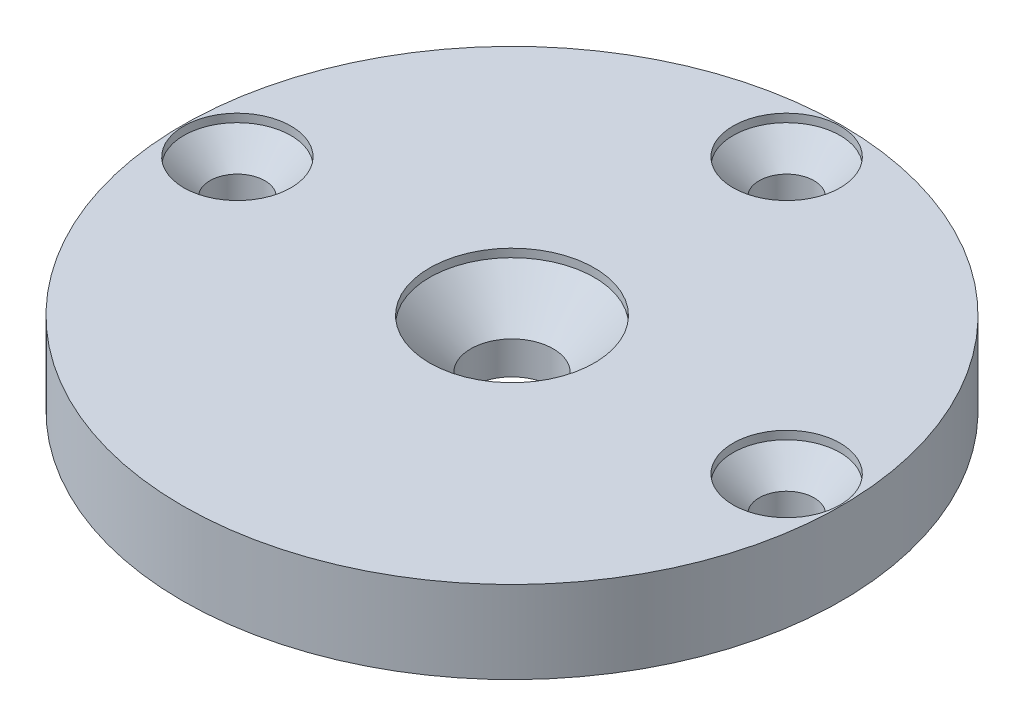
SolidWorks part; units mm, degrees
ref_plane "Front Plane" through (0, 0, 0) normal (0, 0, 1) x (1, 0, 0)
ref_plane "Top Plane" through (0, 0, 0) normal (0, 1, 0) x (1, 0, 0)
ref_plane "Right Plane" through (0, 0, 0) normal (1, 0, 0) x (0, 0, -1)
sketch "Sketch1" plane through (0, 0, 0) normal (0, 1, 0) x (1, 0, 0)
  circle A0 centre (0, 0) radius 12
  circle A1 centre (0, 0) radius 1.5
  circle A2 centre (0, 0) radius 10
  circle A3 centre (-10, 0) radius 1
  circle A4 centre (0, 10) radius 1
  circle A5 centre (10, 0) radius 1
  dimension "D1" = 24
  dimension "D2" = 3
  dimension "D3" = 20
  dimension "D4" = 2
extrude "Boss-Extrude1" add sketch "Sketch1" along normal blind 3 contours A0 A5 A2 A3 A4 | A5 A2 A4 A3 A1
hole_wizard "CSK for M2 Flat Head Machine Screw1" positions "Sketch2" profile "Sketch3" countersink size "M2" standard "ANSI Metric"
sketch "Sketch2" plane through (0, 3, 0) normal (0, 1, 0) x (1, 0, 0)
  point P0 (-10, 0)
  point P3 (0, 10)
  point P6 (10, 0)
sketch "Sketch3" plane through (-10, 3, 0) normal (1, 0, 0) x (0, 0, 1)
  line L0 (0, 0) -> (0, 5.6009)
  line L1 (0, 5.6009) -> (1, 5)
  line L2 (1, 5) -> (1, 1.25)
  line L3 (1, 1.25) -> (1.95, 0.3)
  line L4 (1.95, 0.3) -> (1.95, 0)
  line L6 (1.95, 0) -> (0, 0)
  line L7 (-1, 1.25) -> (-1.95, 0.3) construction
  line L10 (0, 5.6009) -> (-1, 5) construction
  line L11 (0, -6.35) -> (0, 107.95) construction
  dimension "Hole Dia." = 2
  dimension "Hole Depth" = 5
  dimension "C'Sink Dia." = 3.9
  dimension "C'Sink Angle" = 90
  dimension "Drill Angle" = 118
  dimension "Head Clearance" = 0.3
hole_wizard "CSK for M3 Flat Head Machine Screw1" positions "Sketch4" profile "Sketch5" countersink size "M3" standard "ANSI Metric"
sketch "Sketch4" plane through (0, 3, 0) normal (0, 1, 0) x (1, 0, 0)
  point P0 (0, 0)
sketch "Sketch5" plane through (0, 3, 0) normal (1, 0, 0) x (0, 0, 1)
  line L0 (0, 0) -> (0, 5.9013)
  line L1 (0, 5.9013) -> (1.5, 5)
  line L2 (1.5, 5) -> (1.5, 1.8)
  line L3 (1.5, 1.8) -> (3, 0.3)
  line L4 (3, 0.3) -> (3, 0)
  line L6 (3, 0) -> (0, 0)
  line L7 (-1.5, 1.8) -> (-3, 0.3) construction
  line L10 (0, 5.9013) -> (-1.5, 5) construction
  line L11 (0, -6.35) -> (0, 107.95) construction
  dimension "Hole Dia." = 3
  dimension "Hole Depth" = 5
  dimension "C'Sink Dia." = 6
  dimension "C'Sink Angle" = 90
  dimension "Drill Angle" = 118
  dimension "Head Clearance" = 0.3
